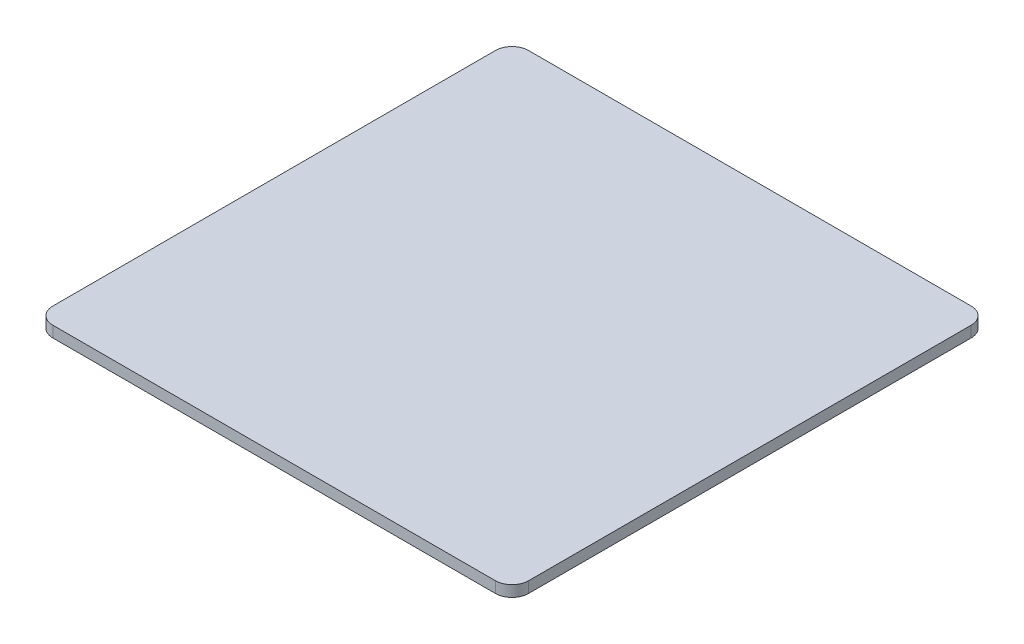
SolidWorks part; units mm, degrees
ref_plane "Front Plane" through (0, 0, 0) normal (0, 0, 1) x (1, 0, 0)
ref_plane "Top Plane" through (0, 0, 0) normal (0, 1, 0) x (1, 0, 0)
ref_plane "Right Plane" through (0, 0, 0) normal (1, 0, 0) x (0, 0, -1)
sketch "Sketch1" plane through (0, 0, 0) normal (0, 1, 0) x (1, 0, 0)
  line L1 (-43, -43) -> (43, -43)
  line L2 (-43, -43) -> (-43, 43)
  line L3 (-43, 43) -> (43, 43)
  line L4 (43, -43) -> (43, 43)
  line L5 (-43, -43) -> (43, 43) construction
  line L6 (-43, 43) -> (43, -43) construction
  point P0 (0, 0)
  dimension "D1" = 86
  dimension "D2" = 86
extrude "Boss-Extrude1" add sketch "Sketch1" along normal blind 2
fillet "Fillet1" radius 3 4 edges at (-43, 1, -43) (43, 1, -43) (43, 1, 43) (-43, 1, 43)
